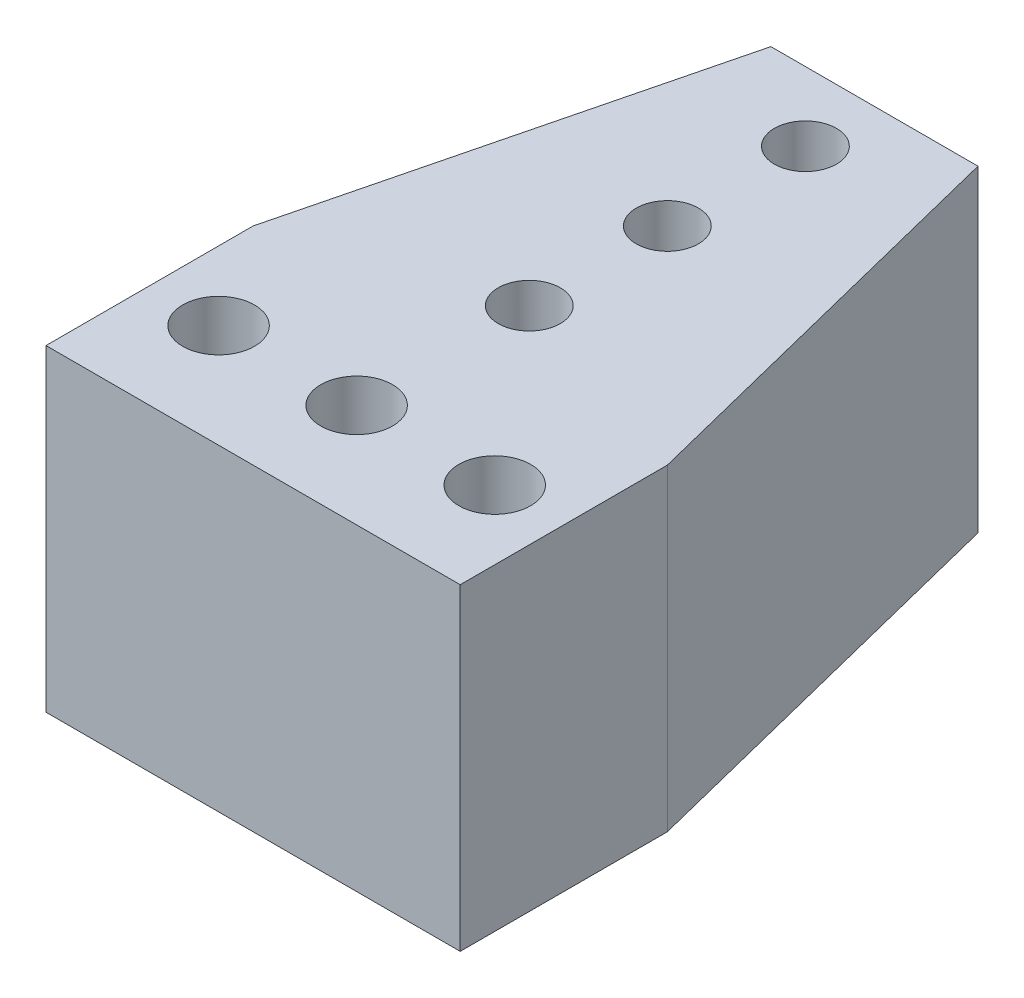
SolidWorks part; units mm, degrees
ref_plane "Front Plane" through (0, 0, 0) normal (0, 0, 1) x (1, 0, 0)
ref_plane "Top Plane" through (0, 0, 0) normal (0, 1, 0) x (1, 0, 0)
ref_plane "Right Plane" through (0, 0, 0) normal (1, 0, 0) x (0, 0, -1)
sketch "Sketch1" plane through (0, 0, 0) normal (0, 1, 0) x (1, 0, 0)
  line L0 (-1000, 0) -> (49000, 0) construction
  line L1 (-15, -7.5) -> (15, -7.5)
  line L2 (-15, -7.5) -> (-15, 7.5)
  line L3 (-15, 7.5) -> (15, 7.5)
  line L4 (15, -7.5) -> (15, 7.5)
  line L5 (-15, -7.5) -> (15, 7.5) construction
  line L6 (-15, 7.5) -> (15, -7.5) construction
  circle A0 centre (0, 0) radius 2.6
  circle A1 centre (10, 0) radius 2.6
  circle A2 centre (-10, 0) radius 2.6
  point P0 (0, 0)
  dimension "D3" = 5.2
  dimension "D4" = 5.2
  dimension "D5" = 5.2
  dimension "D6" = 10
  dimension "D7" = 10
  dimension "D1" = 15
  dimension "D2" = 30
extrude "Boss-Extrude1" add sketch "Sketch1" along normal blind 23
sketch "Sketch2" plane through (0, 23, 0) normal (0, 1, 0) x (1, 0, 0)
  line L0 (15, 7.5) -> (-15, 7.5) construction
  line L1 (7.5, 7.5) -> (-7.5, 7.5)
  line L2 (7.5, 7.5) -> (7.5, 37.5)
  line L3 (7.5, 37.5) -> (-7.5, 37.5)
  line L4 (-7.5, 7.5) -> (-7.5, 37.5)
  dimension "D1" = 30
  dimension "D2" = 15
  dimension "D3" = 7.5
extrude "Boss-Extrude2" add sketch "Sketch2" against normal up to surface (23 mm away) up to face at (10, 0, 2.6)
sketch "Sketch3" plane through (0, 23, 0) normal (0, 1, 0) x (1, 0, 0)
  line L0 (0, -1000) -> (0, 49000) construction
  line L1 (7.5, 37.5) -> (-7.5, 37.5) construction
  circle A0 centre (0, 32.5) radius 2.25
  circle A1 centre (0, 22.5) radius 2.25
  circle A2 centre (0, 12.5) radius 2.25
  dimension "D1" = 5
  dimension "D2" = 4.5
  dimension "D3" = 4.5
  dimension "D4" = 4.5
  dimension "D5" = 10
  dimension "D6" = 10
extrude "Cut-Extrude1" cut sketch "Sketch3" against normal through all
sketch "Sketch4" plane through (0, 23, 0) normal (0, 1, 0) x (1, 0, 0)
  line L0 (-7.5, 37.5) -> (-15, 7.5)
  line L1 (-15, 7.5) -> (-7.5, 7.5)
  line L2 (-7.5, 7.5) -> (-7.5, 37.5)
  line L3 (7.5, 37.5) -> (7.5, 7.5)
  line L4 (7.5, 7.5) -> (15, 7.5)
  line L5 (15, 7.5) -> (7.5, 37.5)
extrude "Boss-Extrude3" add sketch "Sketch4" against normal up to surface (23 mm away) up to face at (0, 0, -14.75)
